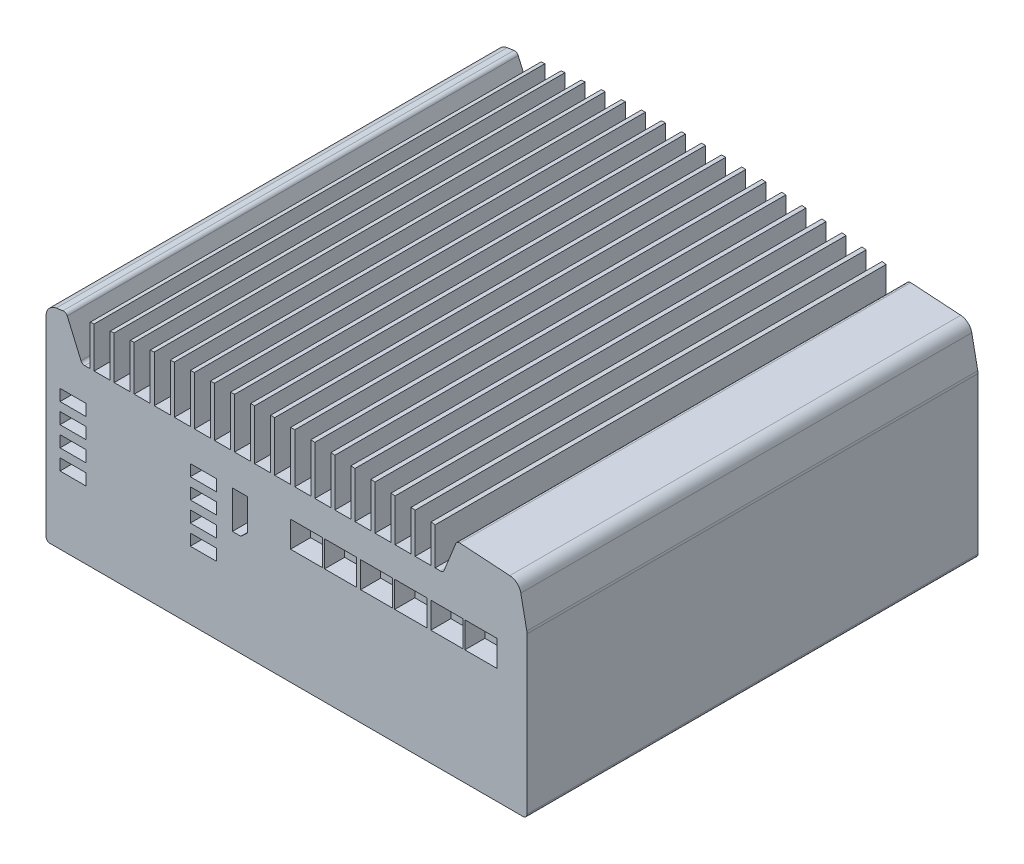
SolidWorks part; units mm, degrees
ref_plane "Plan de face" through (0, 0, 0) normal (0, 0, 1) x (1, 0, 0)
ref_plane "Plan de dessus" through (0, 0, 0) normal (0, 1, 0) x (1, 0, 0)
ref_plane "Plan de droite" through (0, 0, 0) normal (1, 0, 0) x (0, 0, -1)
sketch "Esquisse1" plane through (0, 0, 0) normal (0, 0, 1) x (1, 0, 0)
  line L0 (120, 110.504) -> (120, 0) construction
  line L1 (0, 0) -> (240, 0) construction
  line L2 (0, 0) -> (0, 110.5) construction
  line L3 (0, 110.5) -> (240, 110.5) construction
  line L4 (240, 0) -> (240, 110.5) construction
  line L5 (0, 0) -> (0, 102.5)
  line L6 (0, 102.5) -> (10, 103.9922)
  line L7 (10, 103.9922) -> (18, 85.5)
  line L8 (18, 85.5) -> (22, 85.5)
  line L9 (22, 85.5) -> (22, 105.5771)
  line L10 (22, 105.5771) -> (24, 105.8196)
  line L11 (24, 105.8196) -> (24, 85.5)
  line L12 (24, 85.5) -> (32, 85.5)
  line L13 (32, 85.5) -> (32, 106.7275)
  line L14 (32, 106.7275) -> (34.0035, 106.9395)
  line L15 (34.0035, 106.9395) -> (34.0035, 85.5)
  line L16 (34.0035, 85.5) -> (42.0035, 85.5)
  line L17 (42.0035, 85.5) -> (42.0035, 107.7243)
  line L18 (42.0035, 107.7243) -> (44.0099, 107.9057)
  line L19 (44.0099, 107.9057) -> (44.0099, 85.5)
  line L20 (44.0099, 85.5) -> (52.0099, 85.5)
  line L21 (62.0189, 85.5) -> (62.0189, 109.2586)
  line L22 (62.0189, 109.2586) -> (64.0299, 109.379)
  line L23 (64.0299, 109.379) -> (64.0299, 85.5)
  line L24 (54.0189, 85.5) -> (62.0189, 85.5)
  line L25 (52.0099, 85.5) -> (52.0099, 108.5678)
  line L26 (52.0099, 108.5678) -> (54.0189, 108.7187)
  line L27 (54.0189, 108.7187) -> (54.0189, 85.5)
  line L28 (64.0299, 85.5) -> (72.0299, 85.5)
  line L29 (72.0299, 85.5) -> (72.0299, 109.797)
  line L30 (72.0299, 109.797) -> (74.0426, 109.8868)
  line L31 (74.0426, 109.8868) -> (74.0426, 85.5)
  line L32 (74.0426, 85.5) -> (82.0426, 85.5)
  line L33 (82.0426, 85.5) -> (82.0426, 110.1832)
  line L34 (82.0426, 110.1832) -> (84.0563, 110.2425)
  line L35 (84.0563, 110.2425) -> (84.0563, 85.5)
  line L36 (84.0563, 85.5) -> (92.0563, 85.5)
  line L37 (92.0563, 110.4174) -> (94.0708, 110.4462)
  line L38 (94.0708, 110.4462) -> (94.0708, 85.5)
  line L39 (94.0708, 85.5) -> (102.0708, 85.5)
  line L40 (104.0854, 85.5) -> (112.0854, 85.5)
  line L41 (114.0998, 85.5) -> (122.0998, 85.5)
  line L42 (92.0563, 110.4174) -> (92.0563, 85.5)
  line L43 (124.1135, 85.5) -> (132.1135, 85.5)
  line L44 (102.0708, 85.5) -> (102.0708, 110.4999)
  line L45 (102.0708, 110.4999) -> (104.0854, 110.4981)
  line L46 (104.0854, 110.4981) -> (104.0854, 85.5)
  line L47 (144.1368, 85.5) -> (152.1368, 85.5)
  line L48 (122.0998, 85.5) -> (122.0998, 110.2092)
  line L49 (122.0998, 110.2092) -> (124.1135, 110.1464)
  line L50 (124.1135, 110.1464) -> (124.1135, 85.5)
  line L51 (152.1368, 85.5) -> (152.1368, 108.6326)
  line L52 (112.0854, 85.5) -> (112.0854, 110.4305)
  line L53 (112.0854, 110.4305) -> (114.0998, 110.3982)
  line L54 (114.0998, 110.3982) -> (114.0998, 85.5)
  line L55 (152.1368, 108.6326) -> (154.1455, 108.4782)
  line L56 (132.1135, 85.5) -> (132.1135, 109.8359)
  line L57 (132.1135, 109.8359) -> (134.1259, 109.7426)
  line L58 (134.1259, 109.7426) -> (134.1259, 85.5)
  line L59 (134.1259, 85.5) -> (142.1259, 85.5)
  line L60 (142.1259, 85.5) -> (142.1259, 109.3105)
  line L61 (142.1259, 109.3105) -> (144.1368, 109.1866)
  line L62 (144.1368, 109.1866) -> (144.1368, 85.5)
  line L63 (0, 85.5) -> (240, 85.5) construction
  line L64 (154.1455, 108.4782) -> (154.1455, 85.5)
  line L65 (154.1455, 85.5) -> (162.1455, 85.5)
  line L66 (162.1455, 85.5) -> (162.1455, 107.802)
  line L67 (162.1455, 107.802) -> (164.1516, 107.617)
  line L68 (164.1516, 107.617) -> (164.1516, 85.5)
  line L69 (164.1516, 85.5) -> (172.1516, 85.5)
  line L70 (172.1516, 85.5) -> (172.1516, 106.818)
  line L71 (172.1516, 106.818) -> (174.1547, 106.6026)
  line L72 (174.1547, 106.6026) -> (174.1547, 85.5)
  line L73 (174.1547, 85.5) -> (182.1547, 85.5)
  line L74 (182.1547, 85.5) -> (182.1547, 105.6804)
  line L75 (182.1547, 105.6804) -> (184.1543, 105.4344)
  line L76 (184.1543, 105.4344) -> (184.1543, 85.5)
  line L77 (184.1543, 85.5) -> (192.1543, 85.5)
  line L78 (192.1543, 85.5) -> (192.1543, 104.3883)
  line L79 (192.1543, 104.3883) -> (194.1498, 104.1119)
  line L80 (194.1498, 104.1119) -> (194.1498, 85.5)
  line L81 (194.1498, 85.5) -> (198.1498, 85.5)
  line L82 (0, 102.5) -> (240, 102.5) construction
  line L83 (198.1498, 85.5) -> (205, 102.5)
  line L84 (205, 102.5) -> (236, 100.5)
  line L85 (236, 100.5) -> (240, 80.5)
  line L86 (0, 0) -> (240, 0)
  line L87 (240, 0) -> (240, 80.5)
  line L88 (72, 69.5) -> (85, 69.5)
  line L89 (122, 70.5) -> (138, 70.5)
  line L90 (122, 70.5) -> (122, 57.5)
  line L91 (122, 57.5) -> (138, 57.5)
  line L92 (138, 70.5) -> (138, 57.5)
  line L93 (139, 70.5) -> (155, 70.5)
  line L94 (139, 70.5) -> (139, 57.5)
  line L95 (139, 57.5) -> (155, 57.5)
  line L96 (155, 70.5) -> (155, 57.5)
  line L97 (157, 70.5) -> (173, 70.5)
  line L98 (157, 70.5) -> (157, 57.5)
  line L99 (157, 57.5) -> (173, 57.5)
  line L100 (173, 70.5) -> (173, 57.5)
  line L101 (174, 70.5) -> (190, 70.5)
  line L102 (174, 70.5) -> (174, 57.5)
  line L103 (174, 57.5) -> (190, 57.5)
  line L104 (190, 70.5) -> (190, 57.5)
  line L105 (192, 70.5) -> (208, 70.5)
  line L106 (192, 70.5) -> (192, 57.5)
  line L107 (192, 57.5) -> (208, 57.5)
  line L108 (208, 70.5) -> (208, 57.5)
  line L109 (209, 70.5) -> (225, 70.5)
  line L110 (209, 70.5) -> (209, 57.5)
  line L111 (209, 57.5) -> (225, 57.5)
  line L112 (225, 70.5) -> (225, 57.5)
  line L113 (7, 69.5) -> (20, 69.5)
  line L114 (7, 69.5) -> (7, 63.8)
  line L115 (7, 63.8) -> (20, 63.8)
  line L116 (20, 69.5) -> (20, 63.8)
  line L117 (85, 69.5) -> (85, 63.8)
  line L118 (72, 63.8) -> (85, 63.8)
  line L119 (72, 69.5) -> (72, 63.8)
  line L120 (72, 59.5) -> (85, 59.5)
  line L121 (85, 59.5) -> (85, 53.8)
  line L122 (72, 53.8) -> (85, 53.8)
  line L123 (72, 59.5) -> (72, 53.8)
  line L124 (72, 49.5) -> (85, 49.5)
  line L125 (85, 49.5) -> (85, 43.8)
  line L126 (72, 43.8) -> (85, 43.8)
  line L127 (72, 49.5) -> (72, 43.8)
  line L128 (72, 39.5) -> (85, 39.5)
  line L129 (85, 39.5) -> (85, 33.8)
  line L130 (72, 33.8) -> (85, 33.8)
  line L131 (72, 39.5) -> (72, 33.8)
  line L132 (7, 59.5) -> (20, 59.5)
  line L133 (20, 59.5) -> (20, 53.8)
  line L134 (7, 53.8) -> (20, 53.8)
  line L135 (7, 59.5) -> (7, 53.8)
  line L136 (7, 49.5) -> (20, 49.5)
  line L137 (20, 49.5) -> (20, 43.8)
  line L138 (7, 43.8) -> (20, 43.8)
  line L139 (7, 49.5) -> (7, 43.8)
  line L140 (7, 39.5) -> (20, 39.5)
  line L141 (20, 39.5) -> (20, 33.8)
  line L142 (7, 33.8) -> (20, 33.8)
  line L143 (7, 39.5) -> (7, 33.8)
  line L144 (20.7134, 20.5694) -> (19.7134, 10.5694) construction
  line L145 (19.7134, 10.5694) -> (38.7134, 10.5694) construction
  line L146 (38.7134, 10.5694) -> (37.7134, 20.5694) construction
  line L147 (37.7134, 20.5694) -> (20.7134, 20.5694) construction
  line L148 (29.2134, 20.5694) -> (29.2134, 10.5694) construction
  line L149 (29.2134, 15.5694) -> (51.7399, 15.5694) construction
  line L150 (60.7134, 20.5694) -> (59.7134, 10.5694) construction
  line L151 (59.7134, 10.5694) -> (78.7134, 10.5694) construction
  line L152 (78.7134, 10.5694) -> (77.7134, 20.5694) construction
  line L153 (77.7134, 20.5694) -> (60.7134, 20.5694) construction
  line L154 (93, 69.5) -> (93, 50.7)
  line L155 (93, 50.7) -> (97.2, 50.7)
  line L156 (97.2, 50.7) -> (100.6, 53.8)
  line L157 (100.6, 53.8) -> (100.6, 69.5)
  line L158 (100.6, 69.5) -> (93, 69.5)
  arc A0 (0, 102.5) -> (172.1516, 106.818) centre (102.5, -550.1406) cw construction
  circle A1 centre (41.7134, 15.5694) radius 1.6 construction
  circle A2 centre (16.7134, 15.5694) radius 1.6 construction
  circle A3 centre (56.7134, 15.5694) radius 1.6 construction
  circle A4 centre (81.7134, 15.5694) radius 1.6 construction
  point P169 (85, 66.65)
  dimension "D28" = 3.2
  dimension "D1" = 110.5
  dimension "D2" = 240
  dimension "D3" = 8
  dimension "D4" = 2
  dimension "D5" = 25
  dimension "D6" = 10
  dimension "D7" = 4
  dimension "D8" = 4
  dimension "D9" = 16
  dimension "D10" = 1
  dimension "D11" = 1
  dimension "D12" = 1
  dimension "D13" = 2
  dimension "D14" = 2
  dimension "D15" = 13
  dimension "D16" = 15
  dimension "D17" = 15
  dimension "D20" = 13
  dimension "D21" = 5.7
  dimension "D22" = 10
  dimension "D23" = 65
  dimension "D24" = 19
  dimension "D25" = 17
  dimension "D26" = 10
  dimension "D27" = 25
  dimension "D29" = 18
  dimension "D30" = 10
  dimension "D31" = 4
  dimension "D32" = 35
  dimension "D33" = 2
  dimension "D35" = 5
  dimension "D36" = 18.8
  dimension "D37" = 4.2
  dimension "D38" = 7.6
  dimension "D39" = 15.7
  dimension "D40" = 1
  dimension "D41" = 7
  dimension "D42" = 8
  dimension "D18" = 2
  dimension "D19" = 4
  dimension "D34" = 2
extrude "Boss.-Extru.1" add sketch "Esquisse1" against normal blind 10
fillet "Congé1" radius 6 3 edges at (0, 102.5, -5) (240, 80.5, -5) (236, 100.5, -5)
fillet "Congé2" radius 2 6 edges at (0, 0, -5) (240, 0, -5) (198.1498, 85.5, -5) (205, 102.5, -5) (18, 85.5, -5) (10, 103.9922, -5)
sketch "Esquisse2" plane through (0, 0, -10) normal (0, 0, -1) x (-1, 0, 0)
  line L168 (-238, 0) -> (-2, 0)
  line L169 (0, 2) -> (0, 97.3289)
  line L170 (-5.1145, 103.2632) -> (-8.4796, 103.7653)
  line L171 (-10.6104, 102.5814) -> (-17.4783, 86.7059)
  line L172 (-19.3139, 85.5) -> (-22, 85.5)
  line L173 (-22, 85.5) -> (-22, 105.5771)
  line L174 (-22, 105.5771) -> (-24, 105.8196)
  line L175 (-24, 105.8196) -> (-24, 85.5)
  line L176 (-24, 85.5) -> (-32, 85.5)
  line L177 (-32, 85.5) -> (-32, 106.7275)
  line L178 (-32, 106.7275) -> (-34.0035, 106.9395)
  line L179 (-34.0035, 106.9395) -> (-34.0035, 85.5)
  line L180 (-34.0035, 85.5) -> (-42.0035, 85.5)
  line L181 (-42.0035, 85.5) -> (-42.0035, 107.7243)
  line L182 (-42.0035, 107.7243) -> (-44.0099, 107.9057)
  line L183 (-44.0099, 107.9057) -> (-44.0099, 85.5)
  line L184 (-44.0099, 85.5) -> (-52.0099, 85.5)
  line L185 (-52.0099, 85.5) -> (-52.0099, 108.5678)
  line L186 (-52.0099, 108.5678) -> (-54.0189, 108.7187)
  line L187 (-54.0189, 108.7187) -> (-54.0189, 85.5)
  line L188 (-54.0189, 85.5) -> (-62.0189, 85.5)
  line L189 (-62.0189, 85.5) -> (-62.0189, 109.2586)
  line L190 (-62.0189, 109.2586) -> (-64.0299, 109.379)
  line L191 (-64.0299, 109.379) -> (-64.0299, 85.5)
  line L192 (-64.0299, 85.5) -> (-72.0299, 85.5)
  line L193 (-72.0299, 85.5) -> (-72.0299, 109.797)
  line L194 (-72.0299, 109.797) -> (-74.0426, 109.8868)
  line L195 (-74.0426, 109.8868) -> (-74.0426, 85.5)
  line L196 (-74.0426, 85.5) -> (-82.0426, 85.5)
  line L197 (-82.0426, 85.5) -> (-82.0426, 110.1832)
  line L198 (-82.0426, 110.1832) -> (-84.0563, 110.2425)
  line L199 (-84.0563, 110.2425) -> (-84.0563, 85.5)
  line L200 (-84.0563, 85.5) -> (-92.0563, 85.5)
  line L201 (-92.0563, 85.5) -> (-92.0563, 110.4174)
  line L202 (-92.0563, 110.4174) -> (-94.0708, 110.4462)
  line L203 (-94.0708, 110.4462) -> (-94.0708, 85.5)
  line L204 (-94.0708, 85.5) -> (-102.0708, 85.5)
  line L205 (-102.0708, 85.5) -> (-102.0708, 110.4999)
  line L206 (-102.0708, 110.4999) -> (-104.0854, 110.4981)
  line L207 (-104.0854, 110.4981) -> (-104.0854, 85.5)
  line L208 (-104.0854, 85.5) -> (-112.0854, 85.5)
  line L209 (-112.0854, 85.5) -> (-112.0854, 110.4305)
  line L210 (-112.0854, 110.4305) -> (-114.0998, 110.3982)
  line L211 (-114.0998, 110.3982) -> (-114.0998, 85.5)
  line L212 (-114.0998, 85.5) -> (-122.0998, 85.5)
  line L213 (-122.0998, 85.5) -> (-122.0998, 110.2092)
  line L214 (-122.0998, 110.2092) -> (-124.1135, 110.1464)
  line L215 (-124.1135, 110.1464) -> (-124.1135, 85.5)
  line L216 (-124.1135, 85.5) -> (-132.1135, 85.5)
  line L217 (-132.1135, 85.5) -> (-132.1135, 109.8359)
  line L218 (-132.1135, 109.8359) -> (-134.1259, 109.7426)
  line L219 (-134.1259, 109.7426) -> (-134.1259, 85.5)
  line L220 (-134.1259, 85.5) -> (-142.1259, 85.5)
  line L221 (-142.1259, 85.5) -> (-142.1259, 109.3105)
  line L222 (-142.1259, 109.3105) -> (-144.1368, 109.1866)
  line L223 (-144.1368, 109.1866) -> (-144.1368, 85.5)
  line L224 (-144.1368, 85.5) -> (-152.1368, 85.5)
  line L225 (-152.1368, 85.5) -> (-152.1368, 108.6326)
  line L226 (-152.1368, 108.6326) -> (-154.1455, 108.4782)
  line L227 (-154.1455, 108.4782) -> (-154.1455, 85.5)
  line L228 (-154.1455, 85.5) -> (-162.1455, 85.5)
  line L229 (-162.1455, 85.5) -> (-162.1455, 107.802)
  line L230 (-162.1455, 107.802) -> (-164.1516, 107.617)
  line L231 (-164.1516, 107.617) -> (-164.1516, 85.5)
  line L232 (-164.1516, 85.5) -> (-172.1516, 85.5)
  line L233 (-172.1516, 85.5) -> (-172.1516, 106.818)
  line L234 (-172.1516, 106.818) -> (-174.1547, 106.6026)
  line L235 (-174.1547, 106.6026) -> (-174.1547, 85.5)
  line L236 (-174.1547, 85.5) -> (-182.1547, 85.5)
  line L237 (-182.1547, 85.5) -> (-182.1547, 105.6804)
  line L238 (-182.1547, 105.6804) -> (-184.1543, 105.4344)
  line L239 (-184.1543, 105.4344) -> (-184.1543, 85.5)
  line L240 (-184.1543, 85.5) -> (-192.1543, 85.5)
  line L241 (-192.1543, 85.5) -> (-192.1543, 104.3883)
  line L242 (-192.1543, 104.3883) -> (-194.1498, 104.1119)
  line L243 (-194.1498, 104.1119) -> (-194.1498, 85.5)
  line L244 (-194.1498, 85.5) -> (-196.7995, 85.5)
  line L245 (-198.6545, 86.7525) -> (-204.4595, 101.1585)
  line L246 (-206.4433, 102.4069) -> (-231.4057, 100.7964)
  line L247 (-236.9029, 95.9856) -> (-239.8835, 81.0826)
  line L248 (-240, 79.9059) -> (-240, 2)
  line L249 (-238, 0) -> (-2, 0)
  line L250 (0, 2) -> (0, 97.3289)
  line L251 (-5.1145, 103.2632) -> (-8.4796, 103.7653)
  line L252 (-10.6104, 102.5814) -> (-17.4783, 86.7059)
  line L253 (-19.3139, 85.5) -> (-22, 85.5)
  line L254 (-22, 85.5) -> (-22, 105.5771)
  line L255 (-22, 105.5771) -> (-24, 105.8196)
  line L256 (-24, 105.8196) -> (-24, 85.5)
  line L257 (-24, 85.5) -> (-32, 85.5)
  line L258 (-32, 85.5) -> (-32, 106.7275)
  line L259 (-32, 106.7275) -> (-34.0035, 106.9395)
  line L260 (-34.0035, 106.9395) -> (-34.0035, 85.5)
  line L261 (-34.0035, 85.5) -> (-42.0035, 85.5)
  line L262 (-42.0035, 85.5) -> (-42.0035, 107.7243)
  line L263 (-42.0035, 107.7243) -> (-44.0099, 107.9057)
  line L264 (-44.0099, 107.9057) -> (-44.0099, 85.5)
  line L265 (-44.0099, 85.5) -> (-52.0099, 85.5)
  line L266 (-52.0099, 85.5) -> (-52.0099, 108.5678)
  line L267 (-52.0099, 108.5678) -> (-54.0189, 108.7187)
  line L268 (-54.0189, 108.7187) -> (-54.0189, 85.5)
  line L269 (-54.0189, 85.5) -> (-62.0189, 85.5)
  line L270 (-62.0189, 85.5) -> (-62.0189, 109.2586)
  line L271 (-62.0189, 109.2586) -> (-64.0299, 109.379)
  line L272 (-64.0299, 109.379) -> (-64.0299, 85.5)
  line L273 (-64.0299, 85.5) -> (-72.0299, 85.5)
  line L274 (-72.0299, 85.5) -> (-72.0299, 109.797)
  line L275 (-72.0299, 109.797) -> (-74.0426, 109.8868)
  line L276 (-74.0426, 109.8868) -> (-74.0426, 85.5)
  line L277 (-74.0426, 85.5) -> (-82.0426, 85.5)
  line L278 (-82.0426, 85.5) -> (-82.0426, 110.1832)
  line L279 (-82.0426, 110.1832) -> (-84.0563, 110.2425)
  line L280 (-84.0563, 110.2425) -> (-84.0563, 85.5)
  line L281 (-84.0563, 85.5) -> (-92.0563, 85.5)
  line L282 (-92.0563, 85.5) -> (-92.0563, 110.4174)
  line L283 (-92.0563, 110.4174) -> (-94.0708, 110.4462)
  line L284 (-94.0708, 110.4462) -> (-94.0708, 85.5)
  line L285 (-94.0708, 85.5) -> (-102.0708, 85.5)
  line L286 (-102.0708, 85.5) -> (-102.0708, 110.4999)
  line L287 (-102.0708, 110.4999) -> (-104.0854, 110.4981)
  line L288 (-104.0854, 110.4981) -> (-104.0854, 85.5)
  line L289 (-104.0854, 85.5) -> (-112.0854, 85.5)
  line L290 (-112.0854, 85.5) -> (-112.0854, 110.4305)
  line L291 (-112.0854, 110.4305) -> (-114.0998, 110.3982)
  line L292 (-114.0998, 110.3982) -> (-114.0998, 85.5)
  line L293 (-114.0998, 85.5) -> (-122.0998, 85.5)
  line L294 (-122.0998, 85.5) -> (-122.0998, 110.2092)
  line L295 (-122.0998, 110.2092) -> (-124.1135, 110.1464)
  line L296 (-124.1135, 110.1464) -> (-124.1135, 85.5)
  line L297 (-124.1135, 85.5) -> (-132.1135, 85.5)
  line L298 (-132.1135, 85.5) -> (-132.1135, 109.8359)
  line L299 (-132.1135, 109.8359) -> (-134.1259, 109.7426)
  line L300 (-134.1259, 109.7426) -> (-134.1259, 85.5)
  line L301 (-134.1259, 85.5) -> (-142.1259, 85.5)
  line L302 (-142.1259, 85.5) -> (-142.1259, 109.3105)
  line L303 (-142.1259, 109.3105) -> (-144.1368, 109.1866)
  line L304 (-144.1368, 109.1866) -> (-144.1368, 85.5)
  line L305 (-144.1368, 85.5) -> (-152.1368, 85.5)
  line L306 (-152.1368, 85.5) -> (-152.1368, 108.6326)
  line L307 (-152.1368, 108.6326) -> (-154.1455, 108.4782)
  line L308 (-154.1455, 108.4782) -> (-154.1455, 85.5)
  line L309 (-154.1455, 85.5) -> (-162.1455, 85.5)
  line L310 (-162.1455, 85.5) -> (-162.1455, 107.802)
  line L311 (-162.1455, 107.802) -> (-164.1516, 107.617)
  line L312 (-164.1516, 107.617) -> (-164.1516, 85.5)
  line L313 (-164.1516, 85.5) -> (-172.1516, 85.5)
  line L314 (-172.1516, 85.5) -> (-172.1516, 106.818)
  line L315 (-172.1516, 106.818) -> (-174.1547, 106.6026)
  line L316 (-174.1547, 106.6026) -> (-174.1547, 85.5)
  line L317 (-174.1547, 85.5) -> (-182.1547, 85.5)
  line L318 (-182.1547, 85.5) -> (-182.1547, 105.6804)
  line L319 (-182.1547, 105.6804) -> (-184.1543, 105.4344)
  line L320 (-184.1543, 105.4344) -> (-184.1543, 85.5)
  line L321 (-184.1543, 85.5) -> (-192.1543, 85.5)
  line L322 (-192.1543, 85.5) -> (-192.1543, 104.3883)
  line L323 (-192.1543, 104.3883) -> (-194.1498, 104.1119)
  line L324 (-194.1498, 104.1119) -> (-194.1498, 85.5)
  line L325 (-194.1498, 85.5) -> (-196.7995, 85.5)
  line L326 (-198.6545, 86.7525) -> (-204.4595, 101.1585)
  line L327 (-206.4433, 102.4069) -> (-231.4057, 100.7964)
  line L328 (-236.9029, 95.9856) -> (-239.8835, 81.0826)
  line L329 (-240, 79.9059) -> (-240, 2)
  arc A9 (-204.4595, 101.1585) -> (-206.4433, 102.4069) centre (-206.3145, 100.411) ccw
  arc A10 (-204.4595, 101.1585) -> (-206.4433, 102.4069) centre (-206.3145, 100.411) ccw
  arc A11 (-8.4796, 103.7653) -> (-10.6104, 102.5814) centre (-8.7748, 101.7872) ccw
  arc A12 (-8.4796, 103.7653) -> (-10.6104, 102.5814) centre (-8.7748, 101.7872) ccw
  arc A13 (-19.3139, 85.5) -> (-17.4783, 86.7059) centre (-19.3139, 87.5) ccw
  arc A14 (-19.3139, 85.5) -> (-17.4783, 86.7059) centre (-19.3139, 87.5) ccw
  arc A15 (-2, 0) -> (0, 2) centre (-2, 2) ccw
  arc A16 (0, 97.3289) -> (-5.1145, 103.2632) centre (-6, 97.3289) ccw
  arc A17 (-231.4057, 100.7964) -> (-236.9029, 95.9856) centre (-231.0194, 94.8089) ccw
  arc A18 (-239.8835, 81.0826) -> (-240, 79.9059) centre (-234, 79.9059) ccw
  arc A19 (-240, 2) -> (-238, 0) centre (-238, 2) ccw
  arc A20 (-2, 0) -> (0, 2) centre (-2, 2) ccw
  arc A21 (0, 97.3289) -> (-5.1145, 103.2632) centre (-6, 97.3289) ccw
  arc A22 (-231.4057, 100.7964) -> (-236.9029, 95.9856) centre (-231.0194, 94.8089) ccw
  arc A23 (-239.8835, 81.0826) -> (-240, 79.9059) centre (-234, 79.9059) ccw
  arc A24 (-240, 2) -> (-238, 0) centre (-238, 2) ccw
  arc A25 (-198.6545, 86.7525) -> (-196.7995, 85.5) centre (-196.7995, 87.5) ccw
  arc A26 (-198.6545, 86.7525) -> (-196.7995, 85.5) centre (-196.7995, 87.5) ccw
  dimension "D1" = 0
extrude "Boss.-Extru.2" add sketch "Esquisse2" along normal blind 215
sketch "Esquisse3" plane through (0, 0, -225) normal (0, 0, -1) x (-1, 0, 0)
  line L0 (-58, 70.5) -> (-59, 60.5)
  line L1 (-59, 60.5) -> (-40, 60.5)
  line L2 (-40, 60.5) -> (-41, 70.5)
  line L3 (-41, 70.5) -> (-58, 70.5)
  line L4 (-49.5, 70.5) -> (-49.5, 60.5) construction
  line L5 (-49.5, 65.5) -> (-37, 65.5) construction
  line L22 (-90, 70.5) -> (-91, 60.5)
  line L23 (-91, 60.5) -> (-72, 60.5)
  line L24 (-72, 60.5) -> (-73, 70.5)
  line L25 (-73, 70.5) -> (-90, 70.5)
  line L26 (-113, 70.5) -> (-130, 70.5)
  line L27 (-130, 70.5) -> (-131, 60.5)
  line L28 (-131, 60.5) -> (-112, 60.5)
  line L29 (-112, 60.5) -> (-113, 70.5)
  line L30 (-58, 50.5) -> (-59, 40.5)
  line L31 (-59, 40.5) -> (-40, 40.5)
  line L32 (-40, 40.5) -> (-41, 50.5)
  line L33 (-41, 50.5) -> (-58, 50.5)
  line L34 (0, 2) -> (0, 97.3289) construction
  line L35 (-44.0099, 85.5) -> (-52.0099, 85.5) construction
  line L36 (-29, 43.5) -> (-5, 43.5)
  line L37 (-29, 63.5) -> (-5, 63.5)
  line L38 (-29, 63.5) -> (-29, 71.5)
  line L39 (-29, 71.5) -> (-5, 71.5)
  line L40 (-5, 63.5) -> (-5, 71.5)
  line L41 (-5, 43.5) -> (-5, 51.5)
  line L42 (-29, 51.5) -> (-5, 51.5)
  line L43 (-29, 43.5) -> (-29, 51.5)
  circle A0 centre (-37, 65.5) radius 1.6
  circle A1 centre (-62, 65.5) radius 1.6
  circle A10 centre (-69, 65.5) radius 1.6
  circle A11 centre (-94, 65.5) radius 1.6
  circle A12 centre (-134, 65.5) radius 1.6
  circle A13 centre (-109, 65.5) radius 1.6
  circle A14 centre (-62, 45.5) radius 1.6
  circle A15 centre (-37, 45.5) radius 1.6
  dimension "D5" = 3.2
  dimension "D1" = 25
  dimension "D2" = 17
  dimension "D3" = 19
  dimension "D4" = 10
  dimension "D9" = 37
  dimension "D10" = 15
  dimension "D11" = 20
  dimension "D12" = 32
  dimension "D13" = 40
  dimension "D14" = 5
  dimension "D15" = 8
  dimension "D16" = 1
  dimension "D17" = 24
  dimension "D19" = 20
  dimension "D6" = 2
  dimension "D7" = 2
  dimension "D8" = 2
  dimension "D18" = 2
extrude "Enlèv. mat.-Extru.1" cut sketch "Esquisse3" against normal blind 10
fillet "Congé3" radius 2 16 edges at (58, 50.5, -220) (59, 40.5, -220) (40, 40.5, -220) (41, 50.5, -220) (40, 60.5, -220) (41, 70.5, -220) (59, 60.5, -220) (58, 70.5, -220) (91, 60.5, -220) (72, 60.5, -220) (73, 70.5, -220) (90, 70.5, -220) (131, 60.5, -220) (112, 60.5, -220) (113, 70.5, -220) (130, 70.5, -220)
sketch "Esquisse4" plane through (0, 0, 0) normal (0, -1, 0) x (1, 0, 0)
  line L0 (238, -225) -> (2, -225) construction
  line L1 (240, 0) -> (240, -225) construction
  line B0 (240, 0) -> (240, -225) construction
  line B1 (240, -225) -> (0, -225) construction
  circle B2 centre (228, -200) radius 1.65
  circle B3 centre (228, -25) radius 1.65
  circle B4 centre (12, -200) radius 1.65
  circle B5 centre (12, -25) radius 1.65
sketch_block_instance "Insert_PC_Neousys-1"
sketch_block "Insert_PC_Neousys" parameters "D6"=3.3, "D1"=185, "D2"=35, "D3"=35, "D4"=216, "D5"=175, "D7"=12, "D8"=25, "D9"=12, "D10"=60, "D11"=30
extrude "Enlèv. mat.-Extru.2" cut sketch "Esquisse4" against normal blind 10
